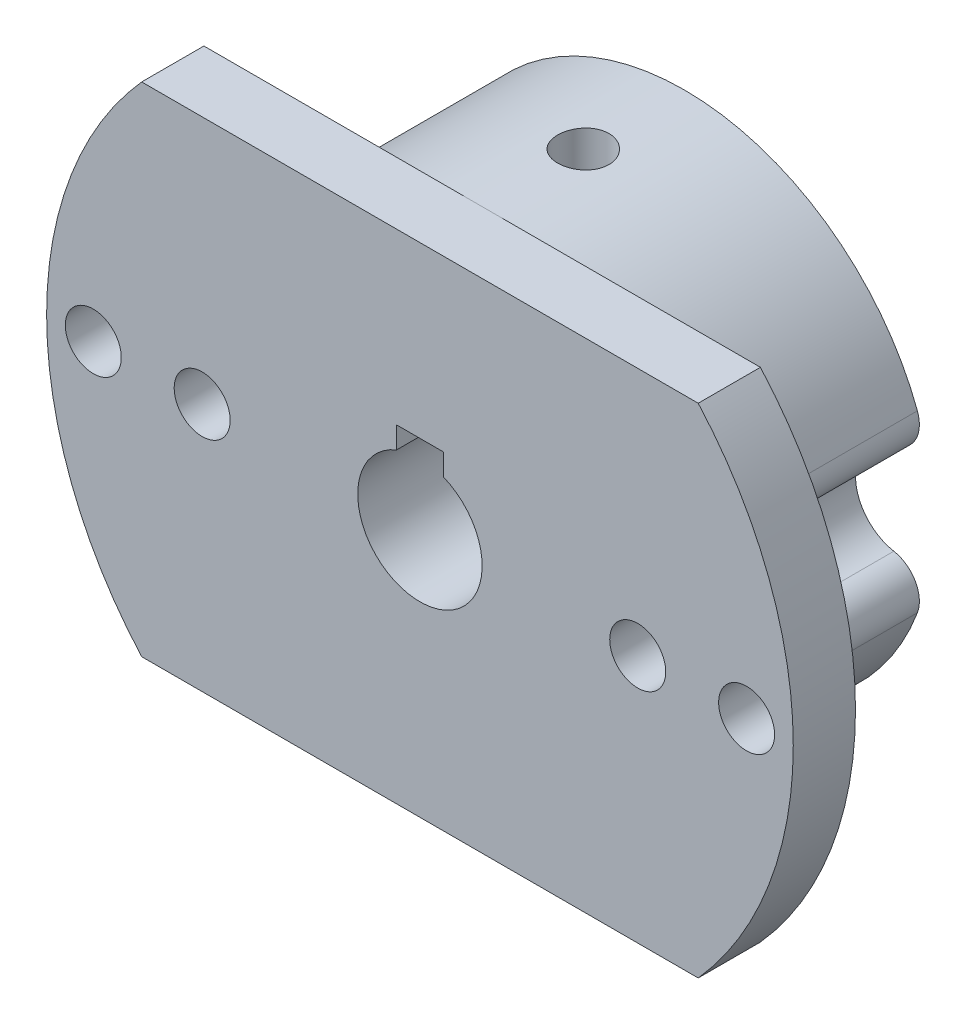
SolidWorks part; units mm, degrees
material "6061 Alloy"
ref_plane "Front" through (0, 0, 0) normal (0, 0, 1) x (1, 0, 0)
ref_plane "Top" through (0, 0, 0) normal (0, 1, 0) x (1, 0, 0)
ref_plane "Right" through (0, 0, 0) normal (1, 0, 0) x (0, 0, -1)
ref_plane "Plane1" through (0, 0, 12) normal (0, 0, -1) x (-1, 0, 0)
sketch "Sketch1" plane through (0, 0, 12) normal (0, 0, -1) x (-1, 0, 0)
  line L0 (17.8885, 16) -> (-17.8885, 16)
  line L1 (-17.8885, -16) -> (17.8885, -16)
  arc A0 (17.8885, -16) -> (17.8885, 16) centre (0, 0) ccw
  arc A1 (-17.8885, 16) -> (-17.8885, -16) centre (0, 0) ccw
extrude "Boss-Extrude1" add sketch "Sketch1" against normal blind 4
ref_plane "Plane2" through (0, 0, 12) normal (0, 0, 1) x (1, 0, 0)
ref_plane "Plane3" through (0, 0, -1) normal (0, 0, -1) x (-1, 0, 0)
sketch "Sketch3" plane through (0, 0, -1) normal (0, 0, -1) x (-1, 0, 0)
  arc A0 (-15.8214, -2.3838) -> (15.8214, -2.3838) centre (0, 0) ccw
  arc A1 (15.8214, -2.3838) -> (15.8214, 2.3838) centre (14, 0) cw
  arc A2 (15.8214, 2.3838) -> (-15.8214, 2.3838) centre (0, 0) ccw
  arc A3 (-15.8214, 2.3838) -> (-15.8214, -2.3838) centre (-14, 0) cw
extrude "Boss-Extrude2" add sketch "Sketch3" against normal up to surface up to plane "Plane2"
hole_wizard "M3 Clearance Hole1" positions "Sketch5" profile "Sketch4" hole size "M3" standard "ANSI Metric" end condition through all
sketch "Sketch5" plane through (0, 0, 12) normal (0, 0, -1) x (-1, 0, 0)
  point P0 (21, 0)
  point P1 (-21, 0)
  point P2 (-14, 0)
  point P3 (14, 0)
sketch "Sketch4" plane through (-21, 0, 12) normal (1, 0, 0) x (0, 1, 0)
  line L0 (0, 0) -> (0, 4)
  line L1 (0, 4) -> (1.8, 4)
  line L2 (1.8, 4) -> (1.8, 0)
  line L5 (1.8, 0) -> (0, 0)
  line L11 (0, -6.35) -> (0, 107.95) construction
  dimension "Thru Hole Dia." = 3.6
  dimension "Thru Hole Depth" = 4
hole_wizard "Ø8.0mm Dowel Hole1" positions "Sketch7" profile "Sketch6" hole size "Ø8.0" standard "ANSI Metric" end condition through all
sketch "Sketch7" plane through (0, 0, -1) normal (0, 0, -1) x (-1, 0, 0)
  point P0 (0, 0)
sketch "Sketch6" plane through (0, 0, -1) normal (1, 0, 0) x (0, 1, 0)
  line L0 (0, 0) -> (0, 17)
  line L1 (0, 17) -> (4, 17)
  line L2 (4, 17) -> (4, 0)
  line L5 (4, 0) -> (0, 0)
  line L11 (0, -6.35) -> (0, 107.95) construction
  dimension "Thru Hole Dia." = 8
  dimension "Thru Hole Depth" = 17
fillet "Fillet1" radius 2 4 edges at (15.8214, 2.3838, 5.5) (15.8214, -2.3838, 5.5) (-15.8214, -2.3838, 5.5) (-15.8214, 2.3838, 5.5)
hole_wizard "M4x0.7 Tapped Hole1" positions "Sketch8" profile "Sketch10" tap size "M4x0.7" standard "ANSI Metric"
sketch "Sketch8" plane through (0, 16, 0) normal (0, 1, 0) x (1, 0, 0)
  line L0 (14.9796, 1) -> (-14.9796, 1) construction
  point P0 (0, -5.5)
  dimension "D1" = 6.5
cosmetic thread "Hole Thread1" parameters "D2"=4
sketch "Sketch10" plane through (0, 16, 5.5) normal (1, 0, 0) x (0, 0, 1)
  line L0 (0, 0) -> (0, 12)
  line L1 (0, 12) -> (1.65, 12)
  line L2 (1.65, 12) -> (1.65, 0)
  line L5 (1.65, 0) -> (0, 0)
  line L11 (0, -6.35) -> (0, 107.95) construction
  dimension "Thru Tap Drill Dia." = 3.3
  dimension "Thru Tap Drill Depth" = 12
hole_wizard "M2.5x0.45 Tapped Hole1" positions "Sketch11" profile "Sketch13" tap size "M2.5x0.45" standard "ANSI Metric"
sketch "Sketch11" plane through (0, -16, 0) normal (0, -1, 0) x (-1, 0, 0)
  line L1 (14.9796, -12) -> (0, -12) construction
  point P0 (0, -4)
  point P2 (0, -10)
  dimension "D1" = 6
  dimension "D2" = 2
sketch "Sketch13" plane through (0, -16, 4) normal (1, 0, 0) x (0, 0, -1)
  line L0 (0, 0) -> (0, 8.6159)
  line L1 (0, 8.6159) -> (1.025, 8)
  line L2 (1.025, 8) -> (1.025, 0)
  line L5 (1.025, 0) -> (0, 0)
  line L10 (0, 8.6159) -> (-1.025, 8) construction
  line L11 (0, -6.35) -> (0, 107.95) construction
  dimension "Tap Drill Dia." = 2.05
  dimension "Tap Drill Depth" = 8
  dimension "Drill Angle" = 118
cosmetic thread "Hole Thread2" parameters "D1"=5, "D2"=2.5
cosmetic thread "Hole Thread3" parameters "D1"=5, "D2"=2.5
sketch "Sketch14" plane through (0, 0, -1) normal (0, 0, -1) x (-1, 0, 0)
  line L0 (0, 0) -> (0, 16) construction
  line L2 (-1.5, 2.1) -> (1.5, 2.1)
  line L3 (-1.5, 2.1) -> (-1.5, 5.1)
  line L4 (-1.5, 5.1) -> (1.5, 5.1)
  line L5 (1.5, 2.1) -> (1.5, 5.1)
  line L6 (-1.5, 2.1) -> (1.5, 5.1) construction
  line L7 (-1.5, 5.1) -> (1.5, 2.1) construction
  point P4 (0, 3.6)
  dimension "D1" = 3
  dimension "D2" = 3
  dimension "D3" = 5.1
extrude "Cut-Extrude1" cut sketch "Sketch14" against normal through all
